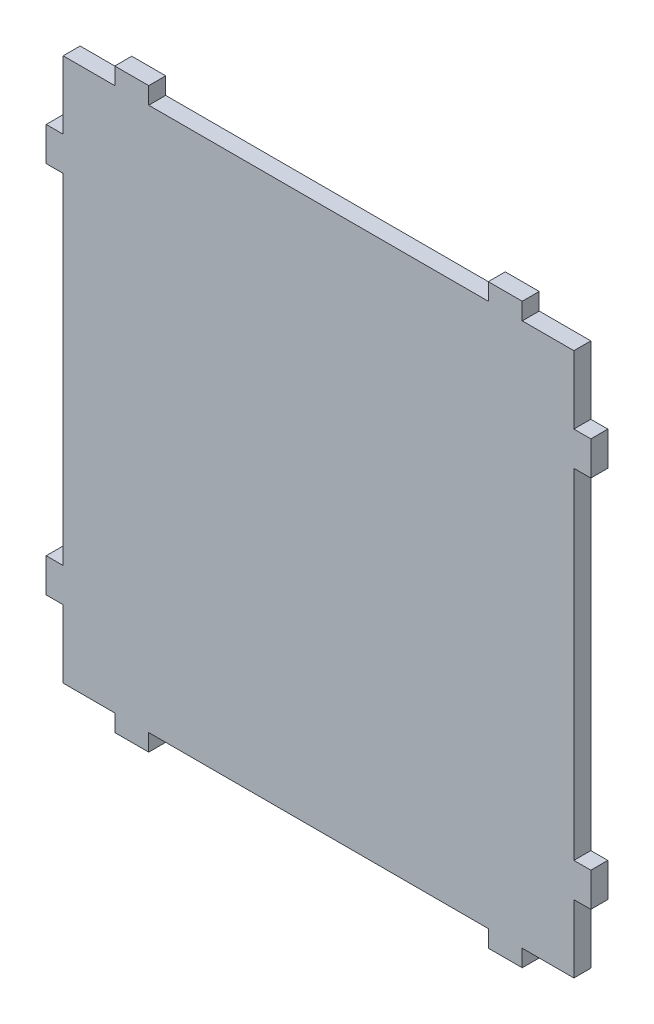
SolidWorks part; units mm, degrees
ref_plane "Front Plane" through (0, 0, 0) normal (0, 0, 1) x (1, 0, 0)
ref_plane "Top Plane" through (0, 0, 0) normal (0, 1, 0) x (1, 0, 0)
ref_plane "Right Plane" through (0, 0, 0) normal (1, 0, 0) x (0, 0, -1)
sketch "Sketch1" plane through (0, 0, 0) normal (0, 0, 1) x (1, 0, 0)
  line L0 (16.002, 0) -> (79.502, 0)
  line L1 (0, 0) -> (9.652, 0)
  line L2 (0, 0) -> (0, -12.7)
  line L3 (0, -101.6) -> (9.652, -101.6)
  line L4 (95.504, -19.05) -> (95.504, -82.55)
  line L6 (9.652, 0) -> (9.652, 3.175)
  line L7 (9.652, 3.175) -> (16.002, 3.175)
  line L8 (16.002, 0) -> (16.002, 3.175)
  line L9 (0, -19.05) -> (0, -82.55)
  line L10 (79.502, 0) -> (79.502, 3.175)
  line L11 (79.502, 3.175) -> (85.852, 3.175)
  line L12 (85.852, 0) -> (85.852, 3.175)
  line L13 (95.504, -12.7) -> (98.679, -12.7)
  line L14 (95.504, -88.9) -> (95.504, -101.6)
  line L15 (95.504, -19.05) -> (98.679, -19.05)
  line L16 (98.679, -12.7) -> (98.679, -19.05)
  line L17 (95.504, -82.55) -> (98.679, -82.55)
  line L18 (85.852, -101.6) -> (95.504, -101.6)
  line L19 (95.504, -88.9) -> (98.679, -88.9)
  line L20 (98.679, -82.55) -> (98.679, -88.9)
  line L21 (16.002, -101.6) -> (79.502, -101.6)
  line L22 (79.502, -101.6) -> (79.502, -104.775)
  line L23 (79.502, -104.775) -> (85.852, -104.775)
  line L24 (85.852, -101.6) -> (85.852, -104.775)
  line L25 (0, -88.9) -> (0, -101.6)
  line L26 (9.652, -101.6) -> (9.652, -104.775)
  line L27 (9.652, -104.775) -> (16.002, -104.775)
  line L28 (16.002, -101.6) -> (16.002, -104.775)
  line L29 (0, -88.9) -> (-3.175, -88.9)
  line L30 (85.852, 0) -> (95.504, 0)
  line L31 (0, -82.55) -> (-3.175, -82.55)
  line L32 (-3.175, -88.9) -> (-3.175, -82.55)
  line L33 (0, -19.05) -> (-3.175, -19.05)
  line L34 (95.504, 0) -> (95.504, -12.7)
  line L35 (0, -12.7) -> (-3.175, -12.7)
  line L36 (-3.175, -19.05) -> (-3.175, -12.7)
  dimension "D3" = 9.652
  dimension "D4" = 6.35
  dimension "D5" = 3.175
  dimension "D6" = 6.35
  dimension "D7" = 3.175
  dimension "D8" = 63.5
  dimension "D9" = 3.175
  dimension "D10" = 6.35
  dimension "D11" = 3.175
  dimension "D12" = 3.175
  dimension "D13" = 6.35
  dimension "D14" = 12.7
  dimension "D15" = 6.35
  dimension "D16" = 3.175
  dimension "D17" = 9.652
  dimension "D18" = 6.35
  dimension "D19" = 9.652
  dimension "D20" = 3.175
  dimension "D21" = 3.175
  dimension "D22" = 6.35
  dimension "D23" = 12.7
  dimension "D24" = 12.7
  dimension "D25" = 6.35
  dimension "D26" = 12.7
  dimension "D27" = 3.175
  dimension "D28" = 63.5
  dimension "D29" = 63.5
  dimension "D30" = 63.5
extrude "Boss-Extrude1" add sketch "Sketch1" along normal blind 3.175 contours L36 L33 L2 L31 L32 L29 L3 L26 L27 L28 L22 L23 L24 L4 L19 L20 L17 L15 L16 L13 L1 L12 L11 L10 L8 L7 L6 L35
